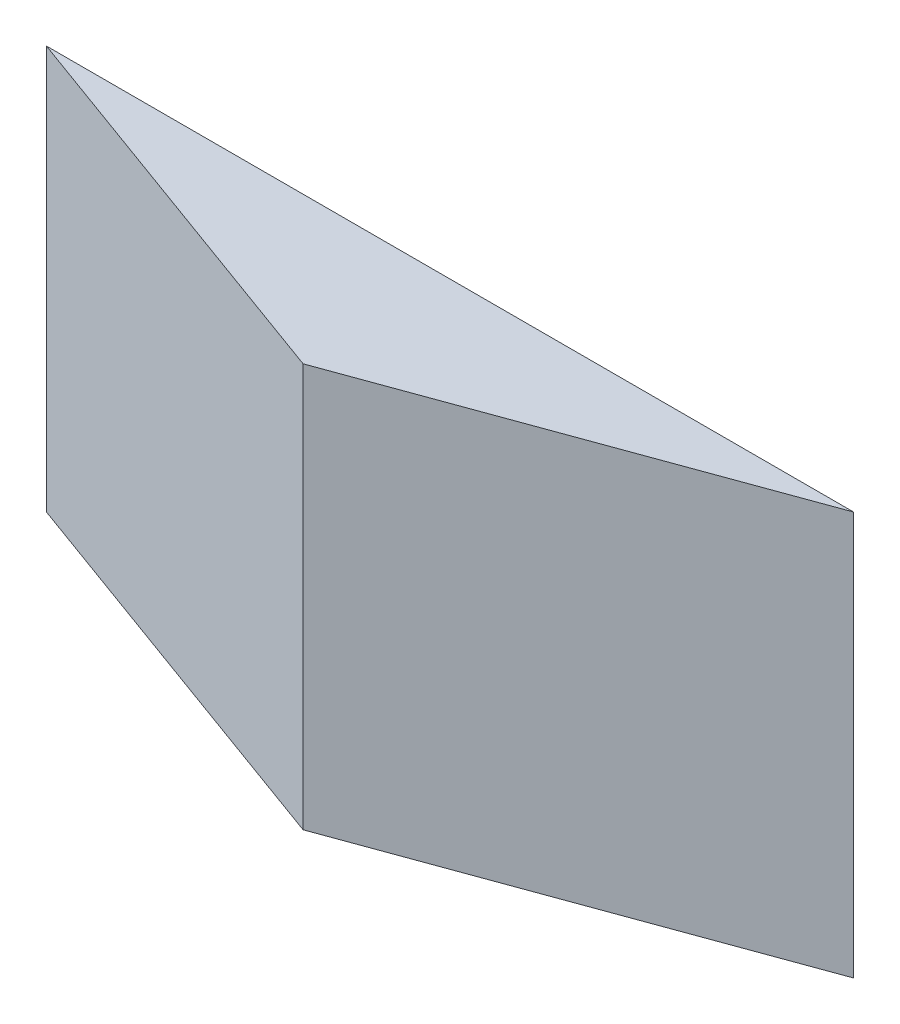
SolidWorks part; units mm, degrees
ref_plane "Přední rovina" through (0, 0, 0) normal (0, 0, 1) x (1, 0, 0)
ref_plane "Horní rovina" through (0, 0, 0) normal (0, 1, 0) x (1, 0, 0)
ref_plane "Pravá rovina" through (0, 0, 0) normal (1, 0, 0) x (0, 0, -1)
sketch "Sketch1" plane through (0, 0, 0) normal (0, 1, 0) x (1, 0, 0)
  line L0 (-20, 0) -> (20, 0)
  line L1 (20, 0) -> (0, -7.2794)
  line L2 (0, -7.2794) -> (0, 0) construction
  line L3 (-20, 0) -> (0, -7.2794)
  dimension "D1" = 20
  dimension "D2" = 20
extrude "Boss-Extrude1" add sketch "Sketch1" along normal blind 20
